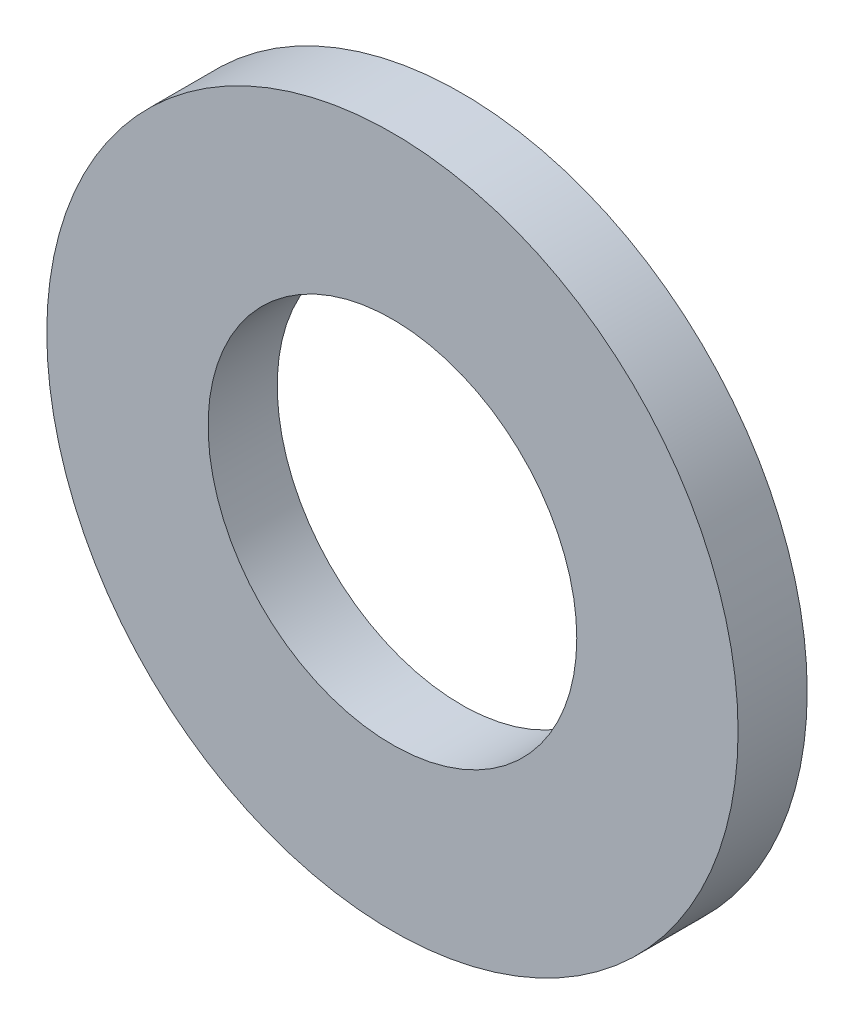
SolidWorks part; units mm, degrees
material "AISI 304"
ref_plane "Front Plane" through (0, 0, 0) normal (0, 0, 1) x (1, 0, 0)
ref_plane "Top Plane" through (0, 0, 0) normal (0, 1, 0) x (1, 0, 0)
ref_plane "Right Plane" through (0, 0, 0) normal (1, 0, 0) x (0, 0, -1)
sketch "Sketch1" plane through (0, 0, 0) normal (0, 0, 1) x (1, 0, 0)
  circle A0 centre (0, 0) radius 3
  circle A1 centre (0, 0) radius 1.6
  dimension "D1" = 3.2
  dimension "D2" = 6
extrude "Boss-Extrude1" add sketch "Sketch1" along normal blind 0.6
equation "\"ID\"=0.003200"
equation "\"OD\"=0.006000"
equation "\"H\"=0.000600"
equation "\"D1@Sketch1\"=\"ID\"*1000"
equation "\"D2@Sketch1\"=\"OD\"*1000"
equation "\"D1@Boss-Extrude1\"=\"H\"*1000"
